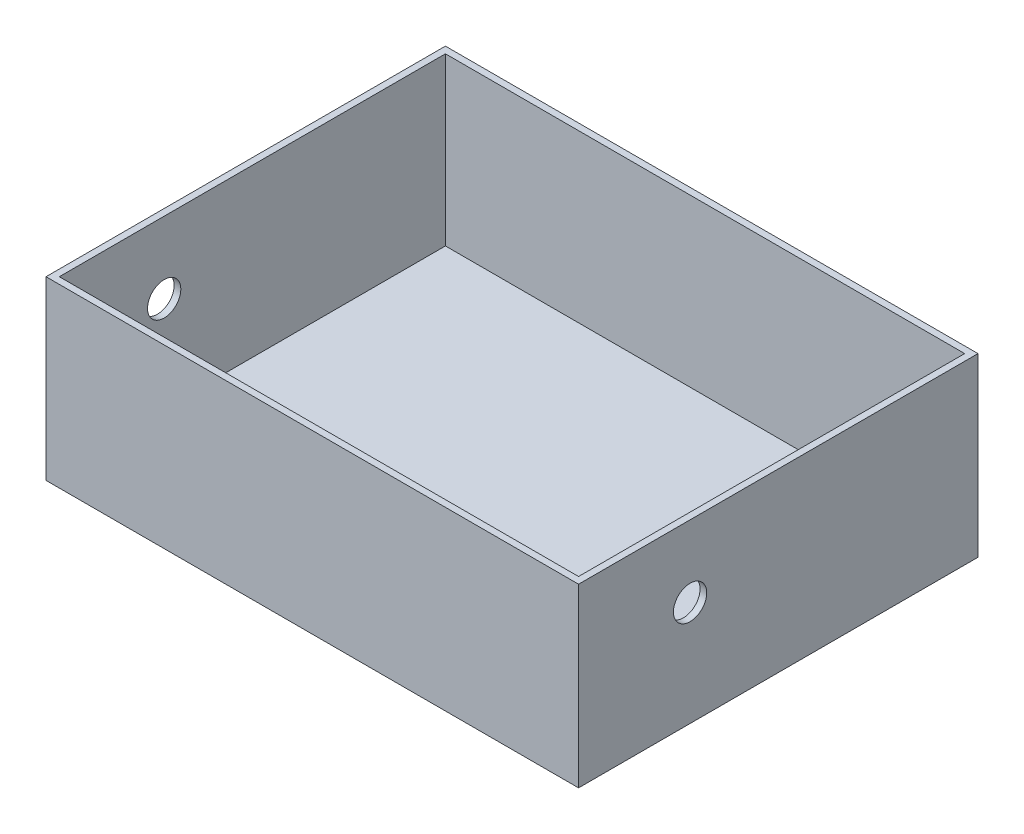
SolidWorks part; units mm, degrees
ref_plane "Front Plane" through (0, 0, 0) normal (0, 0, 1) x (1, 0, 0)
ref_plane "Top Plane" through (0, 0, 0) normal (0, 1, 0) x (1, 0, 0)
ref_plane "Right Plane" through (0, 0, 0) normal (1, 0, 0) x (0, 0, -1)
sketch "Sketch1" plane through (0, 0, 0) normal (0, 1, 0) x (1, 0, 0)
  line L1 (-80, -60) -> (80, -60)
  line L2 (-80, -60) -> (-80, 60)
  line L3 (-80, 60) -> (80, 60)
  line L4 (80, -60) -> (80, 60)
  line L5 (-80, -60) -> (80, 60) construction
  line L6 (-80, 60) -> (80, -60) construction
  point P0 (0, 0)
  dimension "D1" = 160
  dimension "D2" = 120
extrude "Boss-Extrude1" add sketch "Sketch1" along normal blind 3
sketch "Sketch2" plane through (0, 3, 0) normal (0, 1, 0) x (1, 0, 0)
  line L1 (-78, 58) -> (78, 58)
  line L2 (-78, 58) -> (-78, -58)
  line L3 (-78, -58) -> (78, -58)
  line L4 (80, -60) -> (80, 60)
  line L5 (80, 60) -> (-80, 60)
  line L6 (-80, 60) -> (-80, -60)
  line L7 (-80, -60) -> (80, -60)
  line L8 (80, -60) -> (80, 60)
  line L9 (80, 60) -> (-80, 60)
  line L10 (-80, 60) -> (-80, -60)
  line L11 (-80, -60) -> (80, -60)
  line L12 (78, 58) -> (78, -58)
  dimension "D2" = 2
  dimension "D3" = 2
  dimension "D4" = 2
  dimension "D5" = 2
  dimension "D1" = 0
extrude "Boss-Extrude2" add sketch "Sketch2" along normal blind 50
sketch "Sketch3" plane through (80, 0, 0) normal (1, 0, 0) x (0, 0, -1)
  line L0 (33.5, 26.5) -> (-26.5, 26.5) construction
  line L1 (-26.5, 26.5) -> (-26.5, 31.5) construction
  circle A0 centre (-26.5, 31.5) radius 5
  dimension "D3" = 10
  dimension "D1" = 60
  dimension "D2" = 5
extrude "Cut-Extrude1" cut sketch "Sketch3" against normal through all
